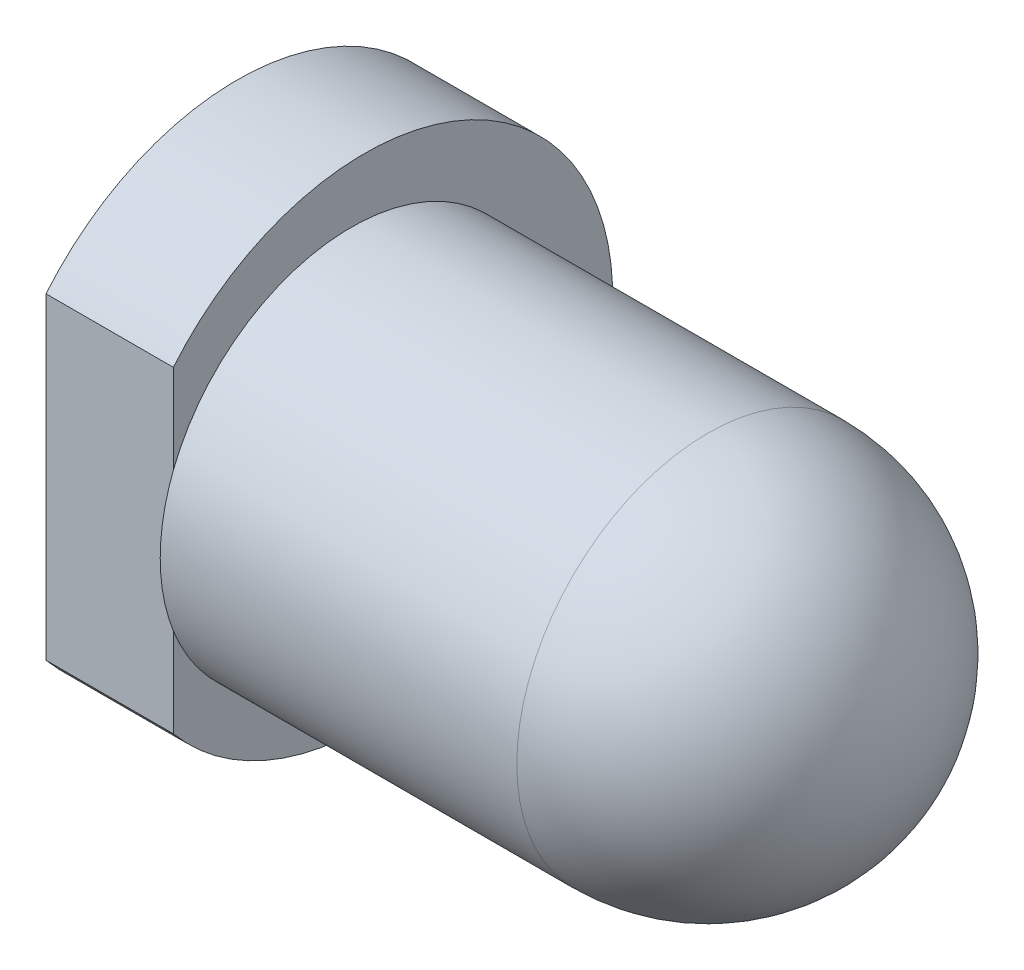
SolidWorks part; units mm, degrees
ref_plane "Спереди" through (0, 0, 0) normal (0, 0, 1) x (1, 0, 0)
ref_plane "Сверху" through (0, 0, 0) normal (0, 1, 0) x (1, 0, 0)
ref_plane "Справа" through (0, 0, 0) normal (1, 0, 0) x (0, 0, -1)
sketch "Эскиз1" plane through (0, 0, 0) normal (1, 0, 0) x (0, 0, -1)
  circle A0 centre (0, 0) radius 1.95
extrude "Бобышка-Вытянуть1" add sketch "Эскиз1" along normal blind 1 contours A0
sketch "Эскиз2" plane through (1, 0, 0) normal (1, 0, 0) x (0, 0, -1)
  circle A0 centre (-0.1031, 0) radius 1.5
extrude "Бобышка-Вытянуть2" add sketch "Эскиз2" along normal blind 4.3
fillet "Скругление1" radius 1.5 1 edges at (5.3, 0, -1.3969)
sketch "Эскиз3" plane through (0, 0, 0) normal (-1, 0, 0) x (0, 0, 1)
  line L0 (0, 0) -> (1.95, 0)
  circle A0 centre (0, 0) radius 1.95 construction
ref_plane "Плоскость2" through (0, 0, 1.95) normal (0, 0, 1) x (1, 0, 0)
sketch "Эскиз4" plane through (0, 0, 1.95) normal (0, 0, 1) x (1, 0, 0)
  line L2 (0, 0) -> (0, 2.8229)
  line L3 (0, 2.8229) -> (1, 2.8229)
  line L4 (1, 0) -> (1, 2.8229)
  line L6 (0, 0) -> (0, -3.257)
  line L7 (0, -3.257) -> (1, -3.257)
  line L8 (1, 0) -> (1, -3.257)
  dimension "D1" = 1
extrude "Вырез-Вытянуть1" cut sketch "Эскиз4" against normal blind 0.45 contours L4 L3 L2 L6 L7 L8
